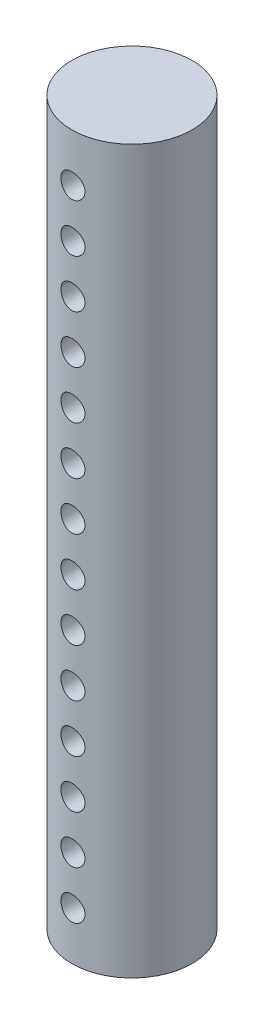
SolidWorks part; units mm, degrees
ref_plane "Front Plane" through (0, 0, 0) normal (0, 0, 1) x (1, 0, 0)
ref_plane "Top Plane" through (0, 0, 0) normal (0, 1, 0) x (1, 0, 0)
ref_plane "Right Plane" through (0, 0, 0) normal (1, 0, 0) x (0, 0, -1)
sketch "Sketch1" plane through (0, 0, 0) normal (0, 1, 0) x (1, 0, 0)
  circle A0 centre (0, 0) radius 25
  dimension "D1" = 50
extrude "Boss-Extrude1" add sketch "Sketch1" along normal blind 300
sketch "Sketch2" plane through (0, 0, 0) normal (0, 0, 1) x (1, 0, 0)
  line L0 (25, 300) -> (-25, 300) construction
  circle A0 centre (0, 280) radius 5
  circle A1 centre (0, 260) radius 5
  circle A2 centre (0, 240) radius 5
  circle A3 centre (0, 220) radius 5
  circle A4 centre (0, 200) radius 5
  circle A5 centre (0, 180) radius 5
  circle A6 centre (0, 160) radius 5
  circle A7 centre (0, 140) radius 5
  circle A8 centre (0, 120) radius 5
  circle A9 centre (0, 100) radius 5
  circle A10 centre (0, 80) radius 5
  circle A11 centre (0, 60) radius 5
  circle A12 centre (0, 40) radius 5
  circle A13 centre (0, 20) radius 5
  dimension "D2" = 10
  dimension "D1" = 20
  dimension "D3" = 14
extrude "Cut-Extrude1" cut sketch "Sketch2" against normal through all both and the other way through all
